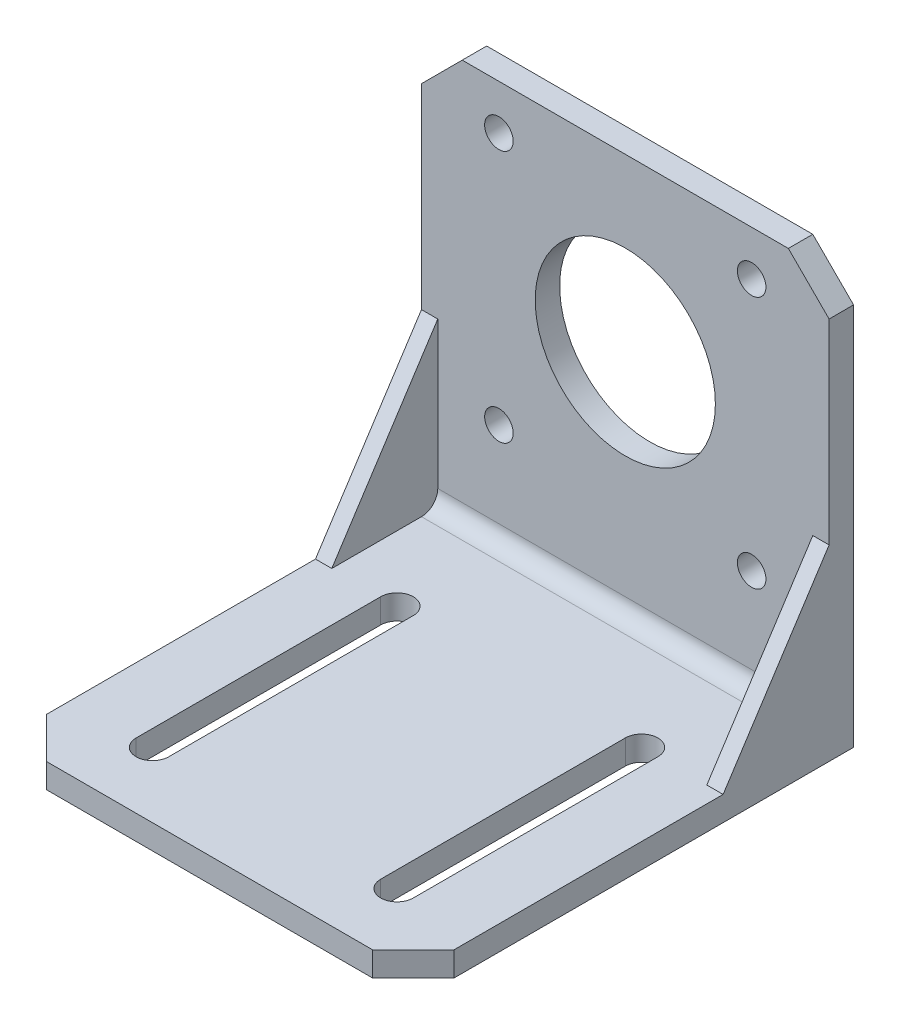
SolidWorks part; units mm, degrees
ref_plane "前视基准面" through (0, 0, 0) normal (0, 0, 1) x (1, 0, 0)
ref_plane "上视基准面" through (0, 0, 0) normal (0, 1, 0) x (1, 0, 0)
ref_plane "右视基准面" through (0, 0, 0) normal (1, 0, 0) x (0, 0, -1)
other "Configuration Table"
sketch "草图1" plane through (0, 0, 0) normal (0, 0, 1) x (1, 0, 0)
  line L0 (0, 24.3091) -> (0, -20.2918) construction
  line L1 (-20, 21) -> (20, 21)
  line L2 (25, 16) -> (25, -28)
  line L3 (15.5, 25.963) -> (15.5, -22.0382) construction
  line L4 (-31.426, 0) -> (30.0865, 0) construction
  line L5 (-25, 16) -> (-25, -28)
  line L6 (20, 21) -> (25, 16)
  line L7 (-25, 16) -> (-20, 21)
  line L8 (-25, -28) -> (25, -28)
  circle A0 centre (0, 0) radius 11.05
  circle A1 centre (15.5, 15.5) radius 1.75
  circle A2 centre (15.5, -15.5) radius 1.75
  circle A3 centre (-15.5, -15.5) radius 1.75
  circle A4 centre (-15.5, 15.5) radius 1.75
  point P6 (25, 21)
  point P20 (-25, 21)
  point P22 (0, 21)
  dimension "D1" = 22.1
  dimension "D6" = 15.5
  dimension "D7" = 3.5
  dimension "D8" = 31
  dimension "D2" = 25
  dimension "D3" = 49
  dimension "D4" = 21
extrude "凸台-拉伸1" add sketch "草图1" against normal blind 3
sketch "草图2" plane through (0, -28, 0) normal (0, -1, 0) x (1, 0, 0)
  line L0 (-25, -3) -> (-25, 46)
  line L1 (0, 36.8787) -> (0, -8.0611) construction
  line L2 (-20, 51) -> (20, 51)
  line L3 (-15, 43) -> (-15, 13) construction
  line L4 (-13, 43) -> (-13, 13)
  line L5 (-17, 43) -> (-17, 13)
  line L6 (-25, 0) -> (25, 0) construction
  line L7 (25, -3) -> (25, 46)
  line L8 (15, 43) -> (15, 13) construction
  line L9 (13, 43) -> (13, 13)
  line L10 (17, 43) -> (17, 13)
  line L11 (-25, -3) -> (25, -3)
  line L12 (-25, 46) -> (-20, 51)
  line L13 (25, 46) -> (20, 51)
  arc A0 (-13, 43) -> (-17, 43) centre (-15, 43) ccw
  arc A1 (-17, 13) -> (-13, 13) centre (-15, 13) ccw
  arc A2 (13, 43) -> (17, 43) centre (15, 43) cw
  arc A3 (17, 13) -> (13, 13) centre (15, 13) cw
  point P1 (-25, 51)
  point P9 (-15, 28)
  point P17 (25, 51)
  point P18 (0, 51)
  point P20 (15, 28)
  dimension "D2" = 2
  dimension "D3" = 13
  dimension "D1" = 54
  dimension "D4" = 8
  dimension "D5" = 30
extrude "凸台-拉伸2" add sketch "草图2" along normal blind 3
sketch "草图3" plane through (-25, 0, 0) normal (-1, 0, 0) x (0, 0, 1)
  line L0 (0, -8) -> (13, -28)
  line L1 (0, 16) -> (0, -28) construction
  line L2 (46, -28) -> (0, -28) construction
  dimension "D1" = 20
  dimension "D2" = 13
rib "筋1" sketch "草图3" sketch "草图3" thickness 2 extrusion direction parallel to sketch draft on no parameters "D1"=2
mirror "镜向1" about plane through (0, 0, 0) normal (1, 0, 0) of "筋1"
fillet "圆角1" radius 2 1 edges at (0, -28, 0)
